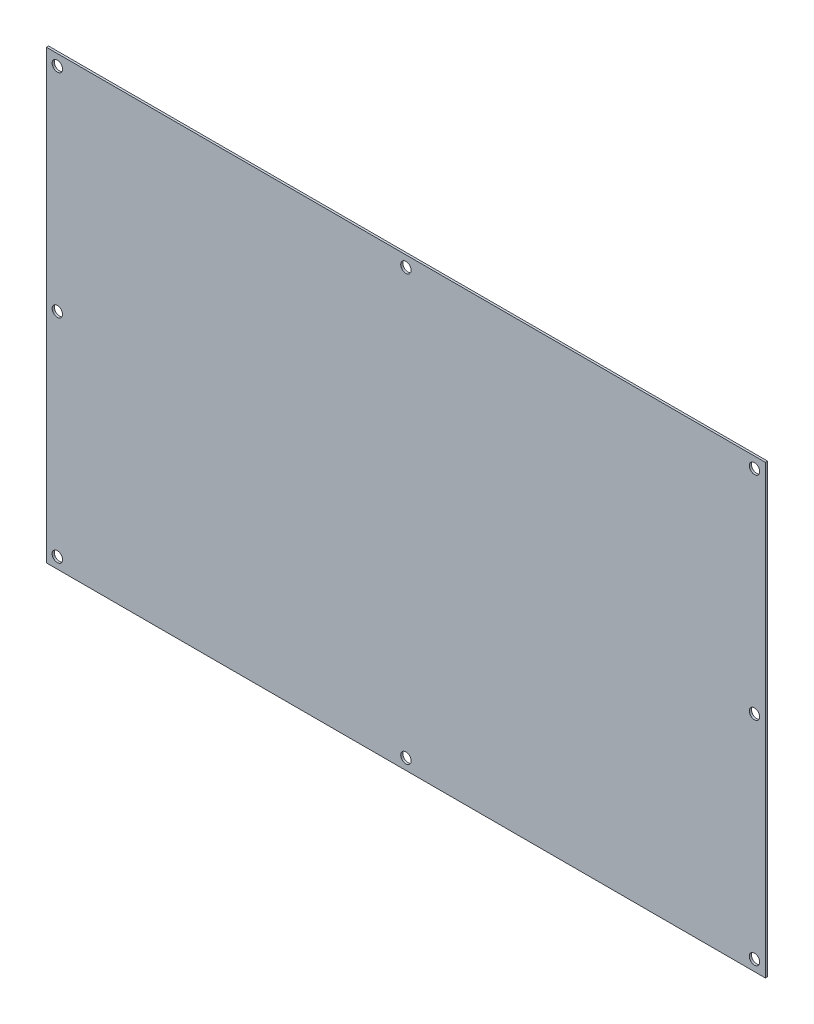
SolidWorks part; units mm, degrees
ref_plane "Alzado" through (0, 0, 0) normal (0, 0, 1) x (1, 0, 0)
ref_plane "Planta" through (0, 0, 0) normal (0, 1, 0) x (1, 0, 0)
ref_plane "Vista lateral" through (0, 0, 0) normal (1, 0, 0) x (0, 0, -1)
sketch "Croquis1" plane through (0, 0, 0) normal (0, 0, 1) x (1, 0, 0)
  line L0 (-52, -225) -> (-52, 201) construction
  line L1 (-52, -12) -> (-27.9748, -12) construction
  line L2 (-382, -217) -> (278, -217)
  line L3 (-382, -217) -> (-382, 193)
  line L4 (-382, 193) -> (278, 193)
  line L5 (278, -217) -> (278, 193)
  line L6 (-382, -217) -> (278, 193) construction
  line L7 (-382, 193) -> (278, -217) construction
  dimension "D1" = 660
  dimension "D2" = 410
extrude "Saliente-Extruir1" add sketch "Croquis1" along normal blind 2
sketch "Croquis2" plane through (0, 0, 2) normal (0, 0, 1) x (1, 0, 0)
  line L0 (-382, -12) -> (278, -12) construction
  line L1 (-382, 193) -> (-382, -217) construction
  line L2 (278, -217) -> (278, 193) construction
  line L3 (278, -12) -> (-52, -12) construction
  line L4 (-52, -12) -> (-52, 193) construction
  line L5 (278, 193) -> (-382, 193) construction
  line L7 (-372, 183) -> (268, 183) construction
  line L8 (-372, 183) -> (-372, -207) construction
  line L9 (-372, -207) -> (268, -207) construction
  line L10 (268, 183) -> (268, -207) construction
  line L11 (-372, 183) -> (268, -207) construction
  line L12 (-372, -207) -> (268, 183) construction
  circle A0 centre (-372, 183) radius 4.765
  circle A1 centre (268, 183) radius 4.765
  circle A2 centre (268, -207) radius 4.765
  circle A3 centre (-372, -207) radius 4.765
  circle A4 centre (-372, -12) radius 4.7625
  circle A5 centre (268, -12) radius 4.7625
  circle A6 centre (-52, 183) radius 4.765
  circle A7 centre (-52, -207) radius 4.765
  dimension "D3" = 9.53
  dimension "D4" = 9.525
  dimension "D5" = 9.53
  dimension "D1" = 10
  dimension "D2" = 10
extrude "Cortar-Extruir2" cut sketch "Croquis2" against normal blind 10
